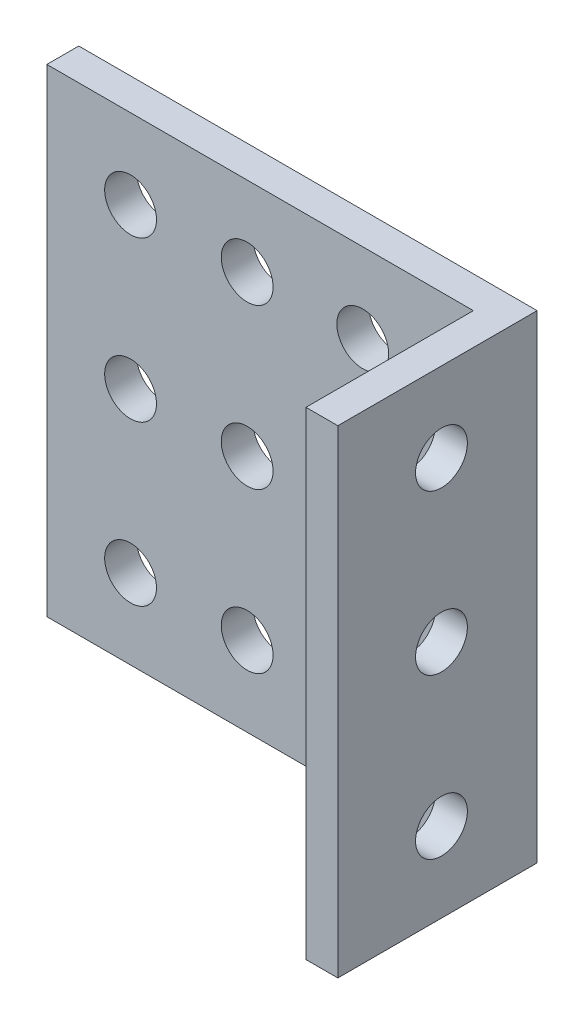
SolidWorks part; units mm, degrees
ref_plane "前视基准面" through (0, 0, 0) normal (0, 0, 1) x (1, 0, 0)
ref_plane "上视基准面" through (0, 0, 0) normal (0, 1, 0) x (1, 0, 0)
ref_plane "右视基准面" through (0, 0, 0) normal (1, 0, 0) x (0, 0, -1)
sketch "草图1" plane through (0, 0, 0) normal (0, 0, 1) x (1, 0, 0)
  line L1 (115, -120) -> (-115, -120)
  line L2 (115, -120) -> (115, 120)
  line L3 (115, 120) -> (-115, 120)
  line L4 (-115, -120) -> (-115, 120)
  line L5 (115, -120) -> (-115, 120) construction
  line L6 (115, 120) -> (-115, -120) construction
  point P0 (0, 0)
  dimension "D1" = 230
  dimension "D2" = 240
extrude "凸台-拉伸1" add sketch "草图1" along normal blind 16
sketch "草图3" plane through (0, 0, 16) normal (0, 0, 1) x (1, 0, 0)
  line L4 (115, 120) -> (-115, 120) construction
  line L5 (115, -120) -> (115, 120) construction
  circle A0 centre (-73, 80) radius 13
  circle A1 centre (-14.5, 80) radius 13
  circle A2 centre (43.5, 80) radius 13
  dimension "D1" = 26
  dimension "D2" = 40
  dimension "D3" = 71.5
  dimension "D4" = 58
  dimension "D5" = 58.5
extrude "切除-拉伸1" cut sketch "草图3" against normal through all
pattern_linear "阵列(线性)1" count 3 spacing 80 along (0, -1, 0) of "切除-拉伸1"
sketch "草图4" plane through (0, 0, 16) normal (0, 0, 1) x (1, 0, 0)
  line L0 (115, 120) -> (-115, 120) construction
  line L1 (115, -120) -> (99, -120)
  line L2 (115, -120) -> (115, 120)
  line L3 (115, 120) -> (99, 120)
  line L4 (99, -120) -> (99, 120)
  dimension "D1" = 16
extrude "凸台-拉伸2" add sketch "草图4" along normal blind 84
sketch "草图5" plane through (99, 0, 0) normal (-1, 0, 0) x (0, 0, 1)
  line L0 (100, 120) -> (100, -120) construction
  line L4 (100, 120) -> (16, 120) construction
  circle A0 centre (48, 80) radius 13
  dimension "D3" = 26
  dimension "D1" = 52
  dimension "D2" = 40
extrude "切除-拉伸2" cut sketch "草图5" against normal through all
pattern_linear "阵列(线性)2" count 3 spacing 80 along (0, -1, 0) of "切除-拉伸2"
